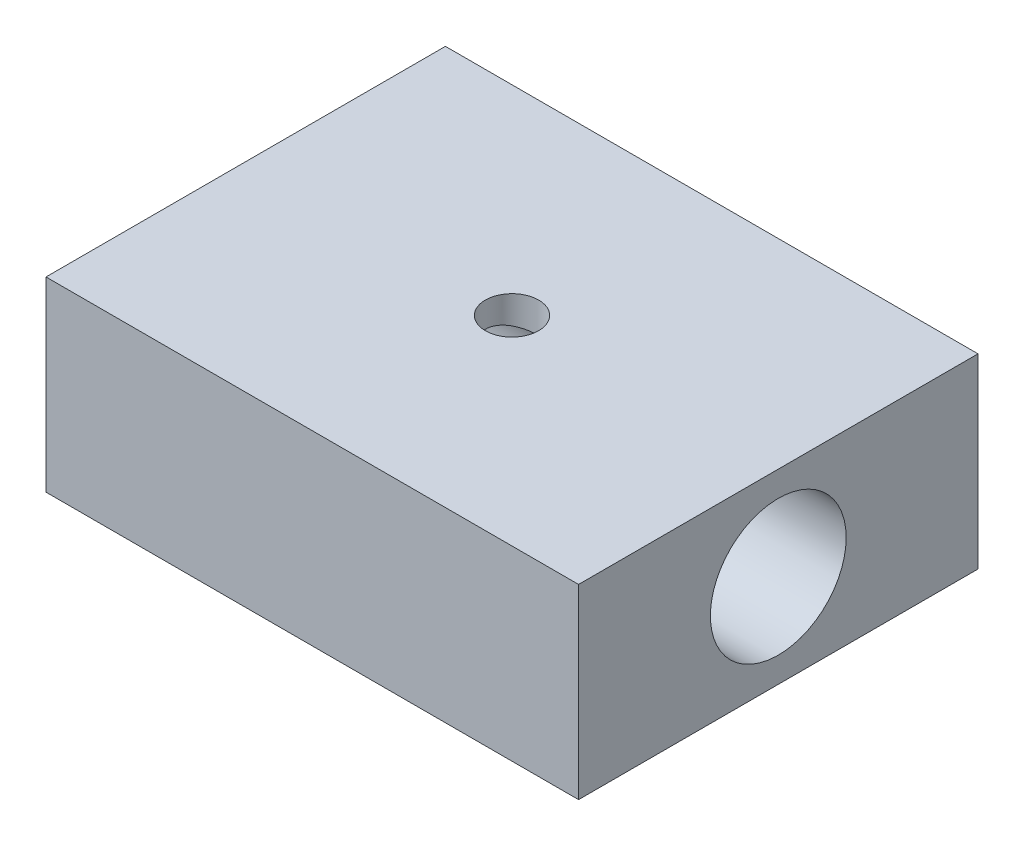
SolidWorks part; units mm, degrees
ref_plane "前基準面" through (0, 0, 0) normal (0, 0, 1) x (1, 0, 0)
ref_plane "上基準面" through (0, 0, 0) normal (0, 1, 0) x (1, 0, 0)
ref_plane "右基準面" through (0, 0, 0) normal (1, 0, 0) x (0, 0, -1)
sketch "草圖2" plane through (0, 0, 0) normal (1, 0, 0) x (0, 0, -1)
  line L0 (0, 7) -> (30, 7) construction
  line L1 (0, 0) -> (30, 0)
  line L2 (0, 0) -> (0, 14)
  line L3 (0, 14) -> (30, 14)
  line L4 (30, 0) -> (30, 14)
  circle A0 centre (15, 7) radius 5.1
  dimension "D1" = 10.2
  dimension "D2" = 30
  dimension "D3" = 14
extrude "填料-伸長1" add sketch "草圖2" along normal blind 40
sketch "草圖3" plane through (0, 14, 0) normal (0, 1, 0) x (1, 0, 0)
  line L0 (0, 15) -> (40, 15) construction
  line L1 (0, 30) -> (0, 0) construction
  line L2 (40, 30) -> (40, 0) construction
  circle A0 centre (20, 15) radius 2
  dimension "D1" = 4
extrude "除料-伸長1" cut sketch "草圖3" against normal through all
